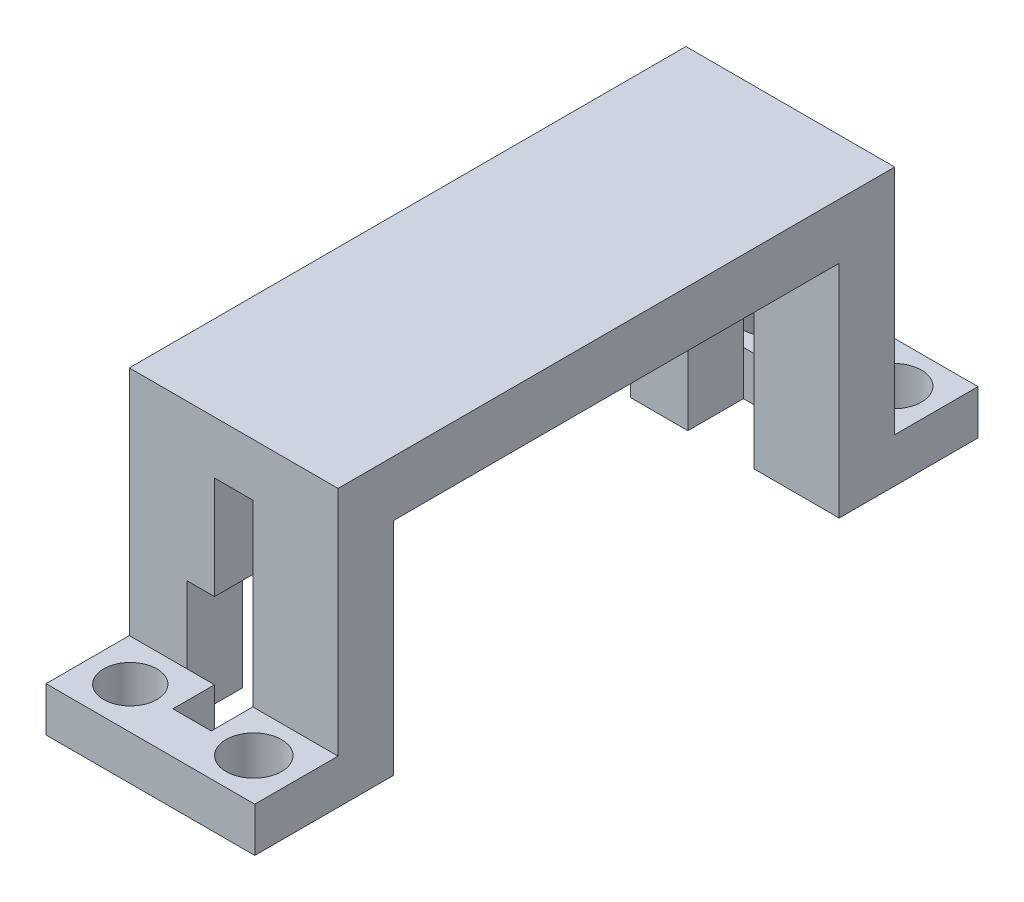
SolidWorks part; units mm, degrees
ref_plane "Front Plane" through (0, 0, 0) normal (0, 0, 1) x (1, 0, 0)
ref_plane "Top Plane" through (0, 0, 0) normal (0, 1, 0) x (1, 0, 0)
ref_plane "Right Plane" through (0, 0, 0) normal (1, 0, 0) x (0, 0, -1)
sketch "Sketch1" plane through (0, 0, 0) normal (1, 0, 0) x (0, 0, -1)
  line L0 (-25.0625, 0) -> (25.0625, 0)
  line L1 (-25.0625, 0) -> (-25.0625, -20.875)
  line L2 (-25.0625, -24.875) -> (-20.0625, -24.875)
  line L3 (-20.0625, -24.875) -> (-20.0625, -5)
  line L4 (-20.0625, -5) -> (20.0625, -5)
  line L5 (20.0625, -5) -> (20.0625, -24.875)
  line L6 (20.0625, -24.875) -> (25.0625, -24.875)
  line L7 (25.0625, -20.875) -> (25.0625, 0)
  line L8 (-20.0625, 0) -> (-20.0625, -5) construction
  line L10 (-25.0625, -24.875) -> (-32.5625, -24.875)
  line L12 (-25.0625, -20.875) -> (-32.5625, -20.875)
  line L13 (-32.5625, -24.875) -> (-32.5625, -20.875)
  line L14 (25.0625, -24.875) -> (32.5625, -24.875)
  line L16 (25.0625, -20.875) -> (32.5625, -20.875)
  line L17 (32.5625, -24.875) -> (32.5625, -20.875)
  point P4 (0, 0)
  dimension "D1" = 40.125
  dimension "D2" = 19.875
  dimension "D3" = 5
  dimension "D4" = 4
  dimension "D5" = 7.5
extrude "Boss-Extrude1" add sketch "Sketch1" along normal blind 18.8
sketch "Sketch2" plane through (0, 0, 32.5625) normal (0, 0, 1) x (1, 0, 0)
  line L0 (0, -24.875) -> (7.675, -24.875) construction
  line L1 (18.8, -24.875) -> (0, -24.875) construction
  line L2 (7.675, -24.875) -> (7.675, -4.75)
  line L3 (7.675, -4.75) -> (11.125, -4.75)
  line L4 (11.125, -4.75) -> (11.125, -24.875)
  line L5 (11.125, -24.875) -> (7.675, -24.875)
  dimension "D1" = 7.675
  dimension "D2" = 3.45
  dimension "D3" = 20.125
extrude "Cut-Extrude1" cut sketch "Sketch2" against normal through all
sketch "Sketch3" plane through (0, -20.875, 0) normal (0, 1, 0) x (1, 0, 0)
  line L0 (2.121, -27.1351) -> (5.554, -30.4899) construction
  line L1 (5.554, -27.1351) -> (2.121, -30.4899) construction
  line L2 (13.246, -27.1351) -> (16.679, -30.4899) construction
  line L3 (16.679, -27.1351) -> (13.246, -30.4899) construction
  line L4 (2.121, 30.4899) -> (5.554, 27.1351) construction
  line L5 (2.121, 27.1351) -> (5.554, 30.4899) construction
  line L6 (13.246, 30.4899) -> (16.679, 27.1351) construction
  line L7 (16.679, 30.4899) -> (13.246, 27.1351) construction
  circle A0 centre (3.8375, -28.8125) radius 2.4
  circle A2 centre (14.9625, -28.8125) radius 2.4
  circle A3 centre (14.9625, 28.8125) radius 2.4
  circle A4 centre (3.8375, 28.8125) radius 2.4
  dimension "D1" = 2
  dimension "D3" = 4.8
  dimension "D2" = 2
extrude "Cut-Extrude2" cut sketch "Sketch3" against normal up to next contours A0 | A2 | A3 | A4
sketch "Sketch4" plane through (7.675, 0, 0) normal (1, 0, 0) x (0, 0, -1)
  line L0 (-20.0625, -24.875) -> (-20.0625, -15.75)
  line L1 (-20.0625, -24.875) -> (-20.0625, -5) construction
  line L2 (-20.0625, -15.75) -> (-20.0625, -14)
  line L3 (-20.0625, -14) -> (-25.0625, -14)
  line L4 (-25.0625, 0) -> (-25.0625, -20.875) construction
  line L5 (-25.0625, -14) -> (-25.0625, -15.75)
  line L7 (-25.0625, -15.75) -> (-25.0625, -24.875)
  line L8 (-32.5625, -24.875) -> (-20.0625, -24.875) construction
  line L9 (-25.0625, -24.875) -> (-20.0625, -24.875)
  dimension "D1" = 9.125
  dimension "D2" = 1.75
sketch "Sketch7" plane through (7.675, 0, 0) normal (1, 0, 0) x (0, 0, -1)
  line L0 (-32.5625, -24.875) -> (-20.0625, -24.875) construction
  line L2 (-32.5625, -20.875) -> (-28.8125, -20.875)
  line L3 (-32.5625, -20.875) -> (-32.5625, -24.875)
  line L4 (-32.5625, -24.875) -> (-28.8125, -24.875)
  line L5 (-28.8125, -20.875) -> (-28.8125, -24.875)
  line L6 (-26.4125, -20.875) -> (-31.2125, -20.875) construction
extrude "Boss-Extrude2" add sketch "Sketch7" along normal up to next
mirror "Mirror1" about plane through (0, 0, 0) normal (0, 0, 1) of "Boss-Extrude2"
extrude "Cut-Extrude8" cut sketch "Sketch4" against normal blind 2.5
mirror "Mirror2" about plane through (0, 0, 0) normal (0, 0, 1) of "Cut-Extrude8", "Mirror1", "Boss-Extrude2"
sketch "Sketch8" plane through (0, -20.875, 0) normal (0, 1, 0) x (1, 0, 0)
  line L0 (17.3625, 28.8125) -> (12.5625, 28.8125) construction
  line L1 (17.3625, -28.8125) -> (12.5625, -28.8125) construction
  circle A0 centre (14.9625, 28.8125) radius 2.5
  circle A1 centre (14.9625, -28.8125) radius 2.5
  dimension "D1" = 5
extrude "Cut-Extrude9" cut sketch "Sketch8" against normal through all
